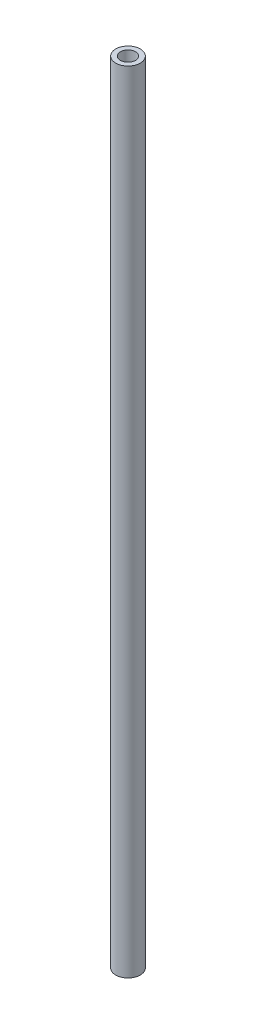
SolidWorks part; units mm, degrees
material "Thornel VCB-20 Carbon Cloth"
ref_plane "Front Plane" through (0, 0, 0) normal (0, 0, 1) x (1, 0, 0)
ref_plane "Top Plane" through (0, 0, 0) normal (0, 1, 0) x (1, 0, 0)
ref_plane "Right Plane" through (0, 0, 0) normal (1, 0, 0) x (0, 0, -1)
sketch "Sketch1" plane through (0, 0, 0) normal (0, 1, 0) x (1, 0, 0)
  circle A0 centre (0, 0) radius 3.048
  circle A1 centre (0, 0) radius 4.953
  dimension "D1" = 6.096
  dimension "D2" = 9.906
extrude "Boss-Extrude1" add sketch "Sketch1" along normal blind 318.4
